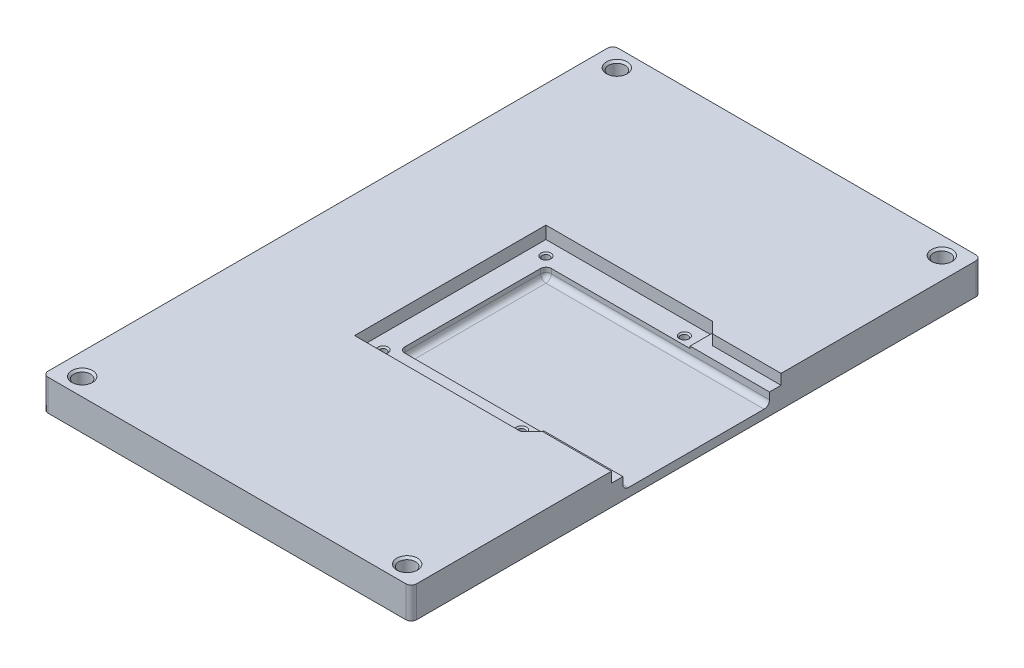
SolidWorks part; units mm, degrees
ref_plane "Front Plane" through (0, 0, 0) normal (0, 0, 1) x (1, 0, 0)
ref_plane "Top Plane" through (0, 0, 0) normal (0, 1, 0) x (1, 0, 0)
ref_plane "Right Plane" through (0, 0, 0) normal (1, 0, 0) x (0, 0, -1)
sketch "Sketch1" plane through (0, 0, 0) normal (0, 1, 0) x (1, 0, 0)
  line L0 (0, -90) -> (0, 90) construction
  line L1 (67.875, 90) -> (-67.875, 90) construction
  line L2 (-67.875, 90) -> (-67.875, -90)
  line L3 (-67.875, 0) -> (67.875, 0) construction
  line L4 (-67.875, 90) -> (-67.875, 103)
  line L5 (-65.875, 105) -> (65.875, 105)
  line L6 (0, 105) -> (0, 90) construction
  line L7 (67.875, 90) -> (67.875, 103)
  line L8 (67.875, 90) -> (67.875, -90)
  line L9 (0, -105) -> (0, -90) construction
  line L10 (67.875, -90) -> (-67.875, -90) construction
  line L11 (67.875, -90) -> (67.875, -103)
  line L12 (-65.875, -105) -> (65.875, -105)
  line L13 (-67.875, -90) -> (-67.875, -103)
  line L14 (-67.875, 93) -> (67.875, 93) construction
  circle A1 centre (-59.875, 98.5) radius 3.075 construction
  circle A2 centre (59.875, 98.5) radius 3.075 construction
  circle A5 centre (59.875, -98.5) radius 3.075 construction
  circle A6 centre (-59.875, -98.5) radius 3.075 construction
  arc A8 (-65.875, -105) -> (-67.875, -103) centre (-65.875, -103) cw
  arc A9 (67.875, -103) -> (65.875, -105) centre (65.875, -103) cw
  arc A10 (67.875, 103) -> (65.875, 105) centre (65.875, 103) ccw
  arc A11 (-67.875, 103) -> (-65.875, 105) centre (-65.875, 103) cw
  point P24 (0, 0)
  point P36 (-67.875, -105)
  point P39 (67.875, -105)
  point P42 (67.875, 105)
  point P45 (-67.875, 105)
  dimension "D10" = 2
  dimension "D3" = 6.15
  dimension "D1" = 67.875
  dimension "D2" = 90
  dimension "D4" = 6.5
  dimension "D6" = 8
  dimension "D7" = 8.5
  dimension "D8" = 12
  dimension "D9" = 3
  dimension "D11" = 105
extrude "Boss-Extrude1" add sketch "Sketch1" along normal blind 11.5
sketch "Sketch3" plane through (0, 11.5, 0) normal (0, 1, 0) x (1, 0, 0)
  line L0 (0, 0) -> (-67.875, 0) construction
  line L1 (-67.875, 103) -> (-67.875, -103) construction
  line L2 (0, 0) -> (0, 105) construction
  line L3 (65.875, 105) -> (-65.875, 105) construction
  line L4 (3.96, -16.3) -> (3.96, 16.3)
  line L5 (-2.46, -17.8) -> (2.46, -17.8)
  line L6 (-3.96, 16.3) -> (-3.96, -16.3)
  line L7 (2.46, 17.8) -> (-2.46, 17.8)
  line L8 (0, 17.8) -> (0, -17.8) construction
  line L9 (13.25, 0) -> (0, 0) construction
  line L10 (16.15, 10.025) -> (10.35, 10.025)
  line L11 (16.15, 10.025) -> (16.15, -10.025)
  line L12 (16.15, -10.025) -> (10.35, -10.025)
  line L13 (10.35, 10.025) -> (10.35, -10.025)
  line L14 (16.15, 10.025) -> (10.35, -10.025) construction
  line L15 (16.15, -10.025) -> (10.35, 10.025) construction
  line L16 (13.25, 0) -> (13.25, 10.025) construction
  line L17 (-16.15, 10.025) -> (-16.15, -10.025)
  line L18 (-16.15, -10.025) -> (-10.35, -10.025)
  line L23 (-16.15, 10.025) -> (-10.35, 10.025)
  line L24 (-10.35, 10.025) -> (-10.35, -10.025)
  arc A0 (-2.46, 17.8) -> (-3.96, 16.3) centre (-2.46, 16.3) ccw
  arc A1 (3.96, 16.3) -> (2.46, 17.8) centre (2.46, 16.3) ccw
  arc A2 (2.46, -17.8) -> (3.96, -16.3) centre (2.46, -16.3) ccw
  arc A3 (-3.96, -16.3) -> (-2.46, -17.8) centre (-2.46, -16.3) ccw
  point P9 (0, 0)
  point P23 (0, 0)
  dimension "D2" = 1.5
  dimension "D1" = 35.6
  dimension "D3" = 7.92
  dimension "D4" = 20.05
  dimension "D5" = 5.8
  dimension "D6" = 13.25
sketch "Sketch4" plane through (0, 11.5, 0) normal (0, 1, 0) x (1, 0, 0)
  circle A0 centre (-59.875, -98.5) radius 3.075 construction
  circle A1 centre (59.875, -98.5) radius 3.075 construction
  circle A2 centre (59.875, 98.5) radius 3.075 construction
  circle A5 centre (-59.875, 98.5) radius 3.075 construction
  circle A8 centre (-59.875, -98.5) radius 3.075
  circle A9 centre (59.875, -98.5) radius 3.075
  circle A10 centre (59.875, 98.5) radius 3.075
  circle A13 centre (-59.875, 98.5) radius 3.075
extrude "Cut-Extrude1" cut sketch "Sketch4" against normal blind 6
sketch "Sketch21" plane through (0, 11.5, 0) normal (0, 1, 0) x (1, 0, 0)
  line L0 (38.5, 35) -> (-22.5, 35) construction
  line L1 (38.5, 35) -> (42.5, 31) construction
  line L2 (-22.5, 35) -> (-22.5, -35) construction
  line L3 (-22.5, 0) -> (0, 0) construction
  line L4 (0, 0) -> (38.5, 0) construction
  line L5 (38.5, -35) -> (38.5, 35) construction
  line L6 (38.5, -35) -> (-22.5, -35) construction
  line L7 (42.5, 31) -> (67.875, 31) construction
  line L8 (67.875, -103) -> (67.875, 103) construction
  line L9 (67.875, 31) -> (67.875, -31)
  line L10 (67.875, 0) -> (38.5, 0) construction
  line L11 (42.5, -31) -> (67.875, -31) construction
  line L12 (38.5, -35) -> (42.5, -31) construction
  line L13 (42.6036, 31.25) -> (67.875, 31.25)
  line L14 (38.6036, 35.25) -> (42.6036, 31.25)
  line L15 (38.6036, 35.25) -> (-22.75, 35.25)
  line L16 (-22.75, 35.25) -> (-22.75, -35.25)
  line L17 (38.6036, -35.25) -> (-22.75, -35.25)
  line L18 (38.6036, -35.25) -> (42.6036, -31.25)
  line L19 (42.6036, -31.25) -> (67.875, -31.25)
  line L20 (67.875, -31.25) -> (67.875, -31)
  line L21 (67.875, 31) -> (67.875, 31.25)
  circle A0 centre (-17.5, 30) radius 1.6 construction
  circle A1 centre (33.5, 30) radius 1.6 construction
  circle A2 centre (33.5, -30) radius 1.6 construction
  circle A3 centre (-17.5, -30) radius 1.6 construction
  dimension "D8" = 3.2
  dimension "D1" = 22.5
  dimension "D2" = 61
  dimension "D3" = 35
  dimension "D4" = 5
  dimension "D5" = 5
  dimension "D6" = 5
  dimension "D7" = 5
  dimension "D9" = 45
  dimension "D10" = 4
  dimension "D12" = 25.375
  dimension "D11" = 0.25
extrude "Cut-Extrude6" cut sketch "Sketch21" against normal blind 4.6
sketch "Sketch24" plane through (0, 6.9, 0) normal (0, 1, 0) x (1, 0, 0)
  line L0 (67.875, 27) -> (-14.5, 27)
  line L2 (-14.5, 27) -> (-14.5, -27)
  line L3 (-14.5, -27) -> (67.875, -27)
  line L4 (67.875, -27) -> (67.875, 27)
  line L8 (38.5, 35) -> (-22.5, 35) construction
  line L10 (-22.5, 35) -> (-22.5, -35) construction
  line L11 (38.5, -35) -> (-22.5, -35) construction
  line L12 (67.875, -31.25) -> (67.875, 31.25) construction
  dimension "D1" = 8
  dimension "D2" = 8
  dimension "D3" = 8
extrude "Cut-Extrude3" cut sketch "Sketch24" against normal blind 3.7 and the other way through all
sketch "Sketch25" plane through (0, 6.9, 0) normal (0, 1, 0) x (1, 0, 0)
  circle A0 centre (33.5, 30) radius 1.35
  circle A1 centre (-17.5, 30) radius 1.35
  circle A2 centre (33.5, -30) radius 1.35
  circle A3 centre (-17.5, -30) radius 1.35
  dimension "D1" = 2.7
extrude "Cut-Extrude4" cut sketch "Sketch25" against normal blind 5
chamfer "Chamfer4" distance 0.5 angle 45 4 edges at (-17.5, 6.9, 31.35) (33.5, 6.9, 31.35) (33.5, 6.9, -28.65) (-17.5, 6.9, -28.65)
fillet "Fillet1" radius 2 5 edges at (26.6875, 3.2, 27) (-14.5, 5.05, 27) (-14.5, 5.05, -27) (-14.5, 3.2, 0) (26.6875, 3.2, -27)
sketch "Sketch26" plane through (0, 6.9, 0) normal (0, 1, 0) x (1, 0, 0)
  line L0 (0, 0) -> (67.875, 0) construction
  line L1 (67.875, -25) -> (67.875, 25) construction
  line L2 (38.6036, 35.25) -> (38.6036, 27)
  line L3 (67.875, 27) -> (-12.5, 27) construction
  line L4 (38.6036, 27) -> (67.875, 27)
  line L5 (67.875, 27) -> (67.875, 31.25)
  line L6 (67.875, 31.25) -> (42.6036, 31.25)
  line L7 (42.6036, 31.25) -> (38.6036, 35.25)
  line L8 (42.6036, -31.25) -> (38.6036, -35.25)
  line L9 (67.875, -31.25) -> (42.6036, -31.25)
  line L10 (67.875, -27) -> (67.875, -31.25)
  line L11 (38.6036, -27) -> (67.875, -27)
  line L12 (38.6036, -35.25) -> (38.6036, -27)
extrude "Boss-Extrude2" add sketch "Sketch26" along normal blind 0.8
chamfer "Chamfer5" distance 0.75 angle 45 4 edges at (59.875, 11.5, 101.575) (-59.875, 11.5, 101.575) (-59.875, 11.5, -95.425) (59.875, 11.5, -95.425)
equation "\"D5@Sketch21\"=\"D4@Sketch21\""
equation "\"D6@Sketch21\"=\"D4@Sketch21\""
equation "\"D7@Sketch21\"=\"D4@Sketch21\""
equation "\"D2@Sketch24\"=\"D1@Sketch24\""
equation "\"D3@Sketch24\"=\"D1@Sketch24\""
